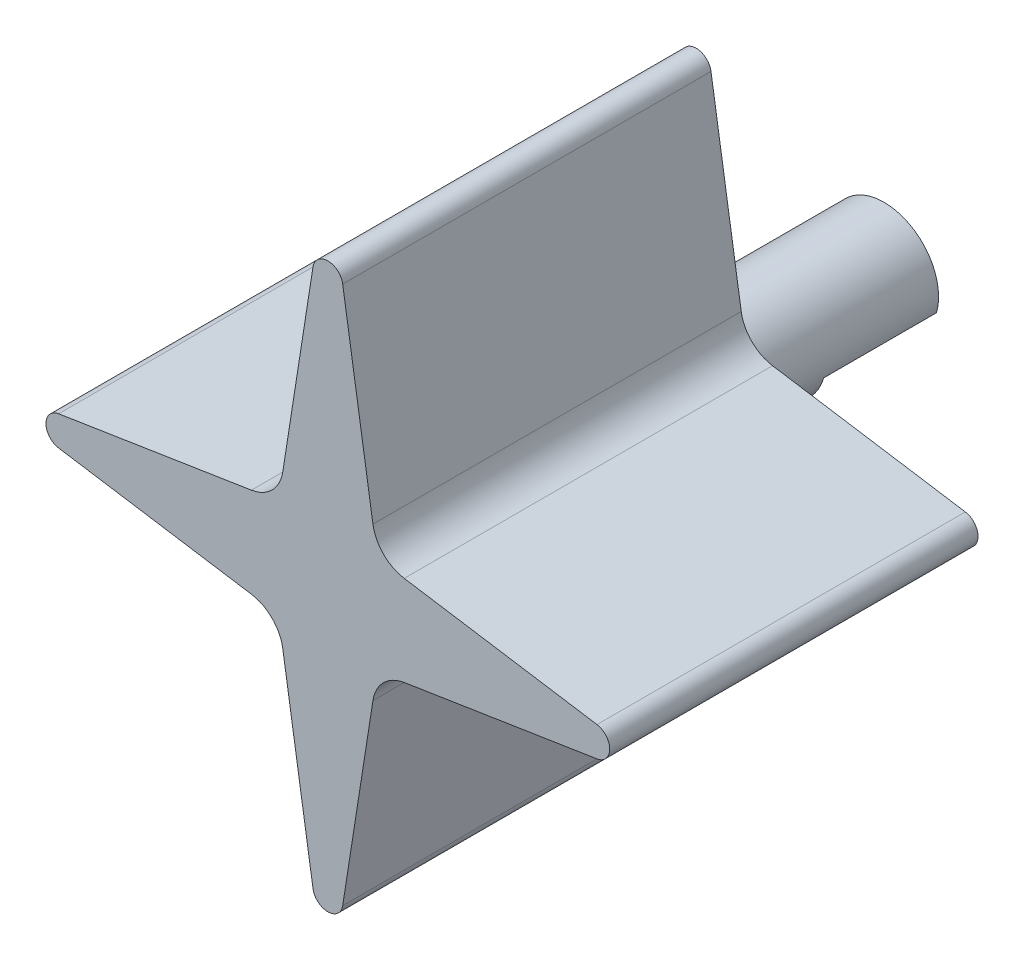
SolidWorks part; units mm, degrees
ref_plane "Front Plane" through (0, 0, 0) normal (0, 0, 1) x (1, 0, 0)
ref_plane "Top Plane" through (0, 0, 0) normal (0, 1, 0) x (1, 0, 0)
ref_plane "Right Plane" through (0, 0, 0) normal (1, 0, 0) x (0, 0, -1)
sketch "Sketch1" plane through (0, 0, 0) normal (0, 0, 1) x (1, 0, 0)
  line L0 (-6.5625, 6.5625) -> (-1.9759, 35.8099)
  line L1 (1.9759, 35.8099) -> (6.5625, 6.5625)
  line L2 (6.5625, 6.5625) -> (35.8099, 1.9759)
  line L3 (35.8099, -1.9759) -> (6.5625, -6.5625)
  line L4 (6.5625, -6.5625) -> (1.9759, -35.8099)
  line L5 (-1.9759, -35.8099) -> (-6.5625, -6.5625)
  line L6 (-6.5625, -6.5625) -> (-35.8099, -1.9759)
  line L7 (-35.8099, 1.9759) -> (-6.5625, 6.5625)
  circle A0 centre (0, 0) radius 50 construction
  circle A1 centre (0, 0) radius 7.5
  arc A2 (-1.9759, 35.8099) -> (1.9759, 35.8099) centre (0, 35.5) cw
  arc A3 (35.8099, 1.9759) -> (35.8099, -1.9759) centre (35.5, 0) cw
  arc A4 (1.9759, -35.8099) -> (-1.9759, -35.8099) centre (0, -35.5) cw
  arc A5 (-35.8099, -1.9759) -> (-35.8099, 1.9759) centre (-35.5, 0) cw
  point P8 (0, 50)
  point P11 (0, 37.5)
  point P29 (0, 0)
  dimension "D1" = 100
  dimension "D2" = 15
  dimension "D3" = 37.5
  dimension "D4" = 2
  dimension "D5" = 4
extrude "Boss-Extrude1" add sketch "Sketch1" along normal blind 49
fillet "Fillet1" radius 5 4 edges at (-6.5625, 6.5625, 24.5) (-6.5625, -6.5625, 24.5) (6.5625, -6.5625, 24.5) (6.5625, 6.5625, 24.5)
sketch "Sketch2" plane through (0, 0, 0) normal (0, 0, -1) x (-1, 0, 0)
  circle A0 centre (0, 0) radius 7.25
  dimension "D1" = 14.5
extrude "Boss-Extrude2" add sketch "Sketch2" along normal blind 25
sketch "Sketch3" plane through (0, 0, -25) normal (0, 0, -1) x (-1, 0, 0)
  line L0 (6.9687, -2) -> (-6.9687, -2)
  circle A0 centre (0, 0) radius 7.25 construction
  arc A1 (6.9687, -2) -> (-6.9687, -2) centre (0, 0) cw
  circle M2 centre (0, 0) radius 7.25
  dimension "D1" = 2
extrude "Cut-Extrude1" cut sketch "Sketch3" against normal blind 15 contours L0 M2
